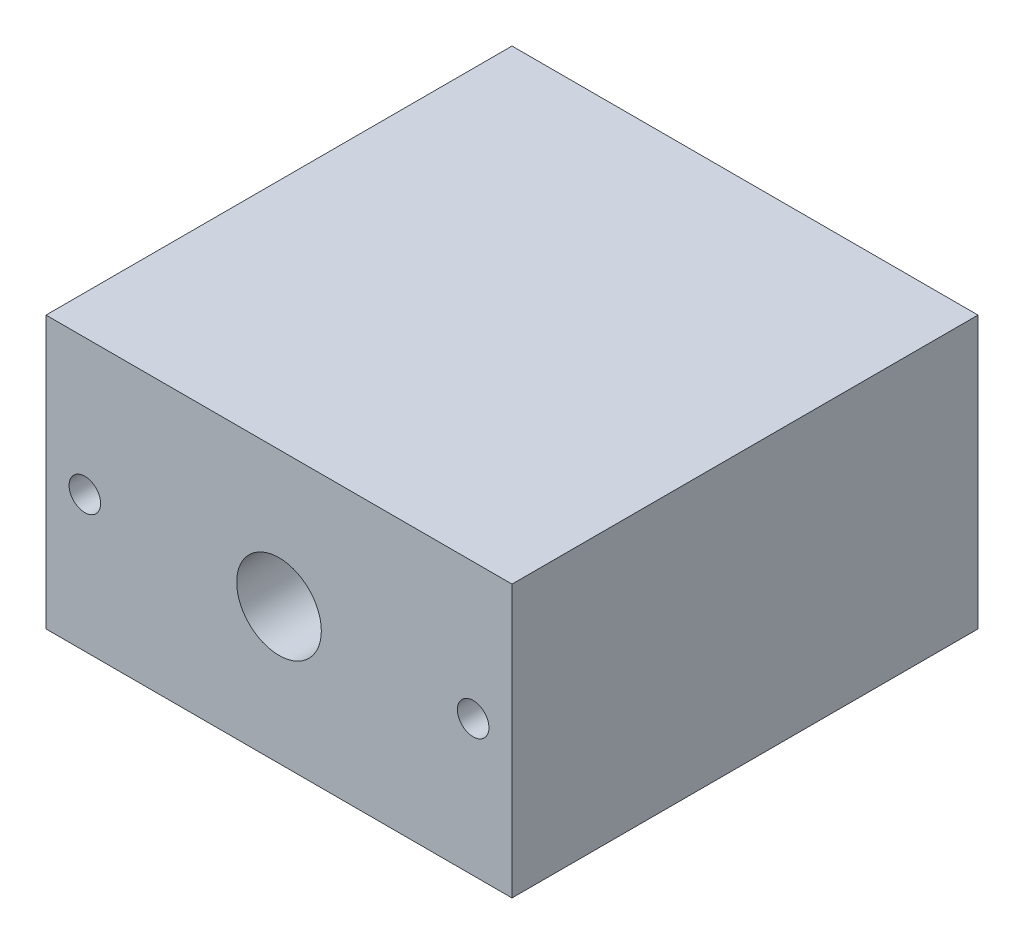
SolidWorks part; units mm, degrees
ref_plane "Front Plane" through (0, 0, 0) normal (0, 0, 1) x (1, 0, 0)
ref_plane "Top Plane" through (0, 0, 0) normal (0, 1, 0) x (1, 0, 0)
ref_plane "Right Plane" through (0, 0, 0) normal (1, 0, 0) x (0, 0, -1)
sketch "Sketch1" plane through (0, 0, 0) normal (0, 0, 1) x (1, 0, 0)
  line L1 (0, 0) -> (152.4, 0)
  line L2 (0, 0) -> (0, 88.9)
  line L3 (0, 88.9) -> (152.4, 88.9)
  line L4 (152.4, 0) -> (152.4, 88.9)
extrude "Boss-Extrude1" add sketch "Sketch1" along normal blind 152.4
sketch "Sketch2" plane through (0, 0, 0) normal (0, 0, 1) x (1, 0, 0)
  circle A0 centre (76.2, 44.45) radius 13.843
extrude "Cut-Extrude1" cut sketch "Sketch2" along normal through all
sketch "Sketch3" plane through (0, 0, 0) normal (0, 0, 1) x (1, 0, 0)
  circle A0 centre (12.7, 44.45) radius 5.1562
  circle A1 centre (139.7, 44.45) radius 5.1562
extrude "Cut-Extrude2" cut sketch "Sketch3" along normal through all
